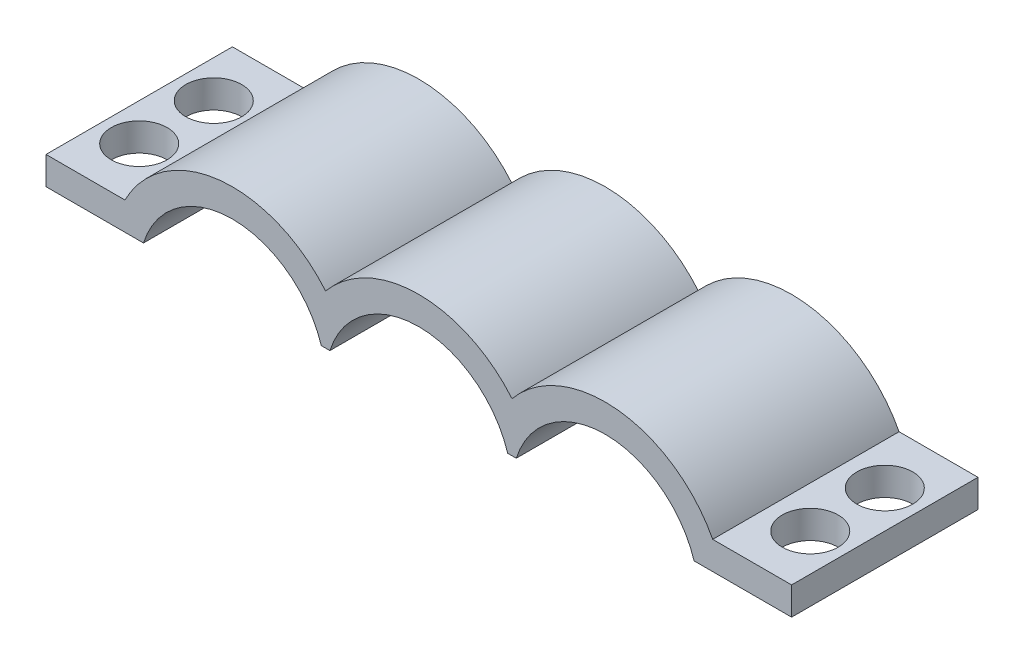
SolidWorks part; units mm, degrees
material "Hexcel AS4C (3000 丝)"
ref_plane "前视基准面" through (0, 0, 0) normal (0, 0, 1) x (1, 0, 0)
ref_plane "上视基准面" through (0, 0, 0) normal (0, 1, 0) x (1, 0, 0)
ref_plane "右视基准面" through (0, 0, 0) normal (1, 0, 0) x (0, 0, -1)
other "Configuration Table"
sketch "草图1" plane through (0, 0, 0) normal (0, 0, 1) x (1, 0, 0)
  line L0 (20, 0) -> (13889.7432, 0) construction
  line L1 (-20, 1.5) -> (-20, 3)
  line L4 (20, 1.5) -> (14.7697, 1.5)
  line L6 (5.2303, 1.5) -> (4.7697, 1.5)
  line L7 (-4.7697, 1.5) -> (-5.2303, 1.5)
  line L8 (-20, 3) -> (-15.7663, 3)
  line L9 (5.0142, -0.3761) -> (4.986, -0.3739) construction
  line L10 (-14.7697, 1.5) -> (-20, 1.5)
  line L11 (0, -1000) -> (0, 49000) construction
  line L12 (20, 1.5) -> (20, 3)
  line L13 (20, 3) -> (15.7663, 3)
  arc A2 (-5.2303, 1.5) -> (-14.7697, 1.5) centre (-10, 0) ccw
  arc A3 (-5, 4.1533) -> (-15.7663, 3) centre (-10, 0) ccw
  arc A6 (14.7697, 1.5) -> (5.2303, 1.5) centre (10, 0) ccw
  circle A7 centre (-10, 0) radius 6.5 construction
  circle A8 centre (-10, 0) radius 5 construction
  arc A9 (15.7663, 3) -> (5, 4.1533) centre (10, 0) ccw
  arc A11 (5, 4.1533) -> (-5, 4.1533) centre (0, 0) ccw
  arc A12 (4.7697, 1.5) -> (-4.7697, 1.5) centre (0, 0) ccw
  dimension "D2" = 10
  dimension "D5" = 40
  dimension "D8" = 1.5
  dimension "D6" = 1.5
extrude "凸台-拉伸1" add sketch "草图1" along normal blind 10
sketch "草图2" plane through (0, 3, 0) normal (0, 1, 0) x (1, 0, 0)
  line L0 (-1020, -5) -> (48980, -5) construction
  line L1 (-20, -10) -> (-20, 0) construction
  line L2 (0, -1000) -> (0, 49000) construction
  line L3 (5, 0) -> (-5, 0) construction
  circle A0 centre (-18, -3) radius 1.5
  circle A1 centre (-18, -7) radius 1.5
  circle A2 centre (18, -7) radius 1.5
  circle A3 centre (18, -3) radius 1.5
  point P5 (-20, -5)
  point P12 (0, 0)
  dimension "D1" = 3
  dimension "D2" = 2
  dimension "D3" = 2
extrude "切除-拉伸1" cut sketch "草图2" against normal blind 10
